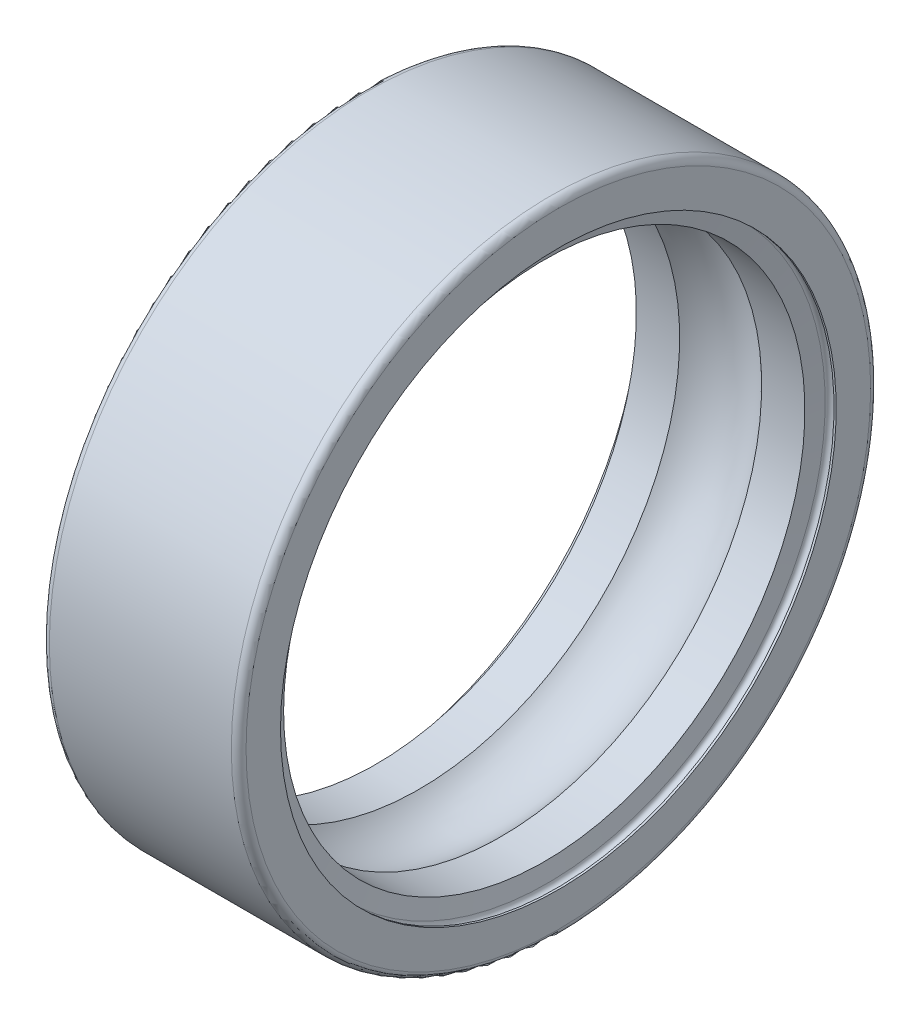
SolidWorks part; units mm, degrees
material "Chrome Stainless Steel"
ref_plane "Front Plane" through (0, 0, 0) normal (0, 0, 1) x (1, 0, 0)
ref_plane "Top Plane" through (0, 0, 0) normal (0, 1, 0) x (1, 0, 0)
ref_plane "Right Plane" through (0, 0, 0) normal (1, 0, 0) x (0, 0, -1)
ref_plane "Plane1" through (0, 0, 0) normal (0, 0, 1) x (1, 0, 0)
sketch "Sketch1" plane through (0, 0, 0) normal (0, 0, 1) x (1, 0, 0)
  line L0 (0, 11.3) -> (0.09, 11.3)
  line L1 (0.45, 11.3) -> (0.5734, 10.6)
  line L2 (0.5734, 10.6) -> (2.3329, 10.6)
  line L3 (5.6671, 10.6) -> (7.4266, 10.6)
  line L4 (7.4266, 10.6) -> (7.55, 11.3)
  line L5 (7.91, 11.3) -> (8, 11.3)
  line L6 (8, 11.3) -> (8, 12.7)
  line L7 (7.7, 13) -> (0.3, 13)
  line L8 (0, 12.7) -> (0, 11.3)
  line L9 (50, 0) -> (-50, 0) construction
  arc A0 (0.09, 11.3) -> (0.45, 11.3) centre (0.27, 11.3) cw
  arc A1 (2.3329, 10.6) -> (5.6671, 10.6) centre (4, 8.9) cw
  arc A2 (7.55, 11.3) -> (7.91, 11.3) centre (7.73, 11.3) cw
  arc A3 (8, 12.7) -> (7.7, 13) centre (7.7, 12.7) ccw
  arc A4 (0.3, 13) -> (0, 12.7) centre (0.3, 12.7) ccw
revolve "Revolve1" add sketch "Sketch1" angle 360 about L9
